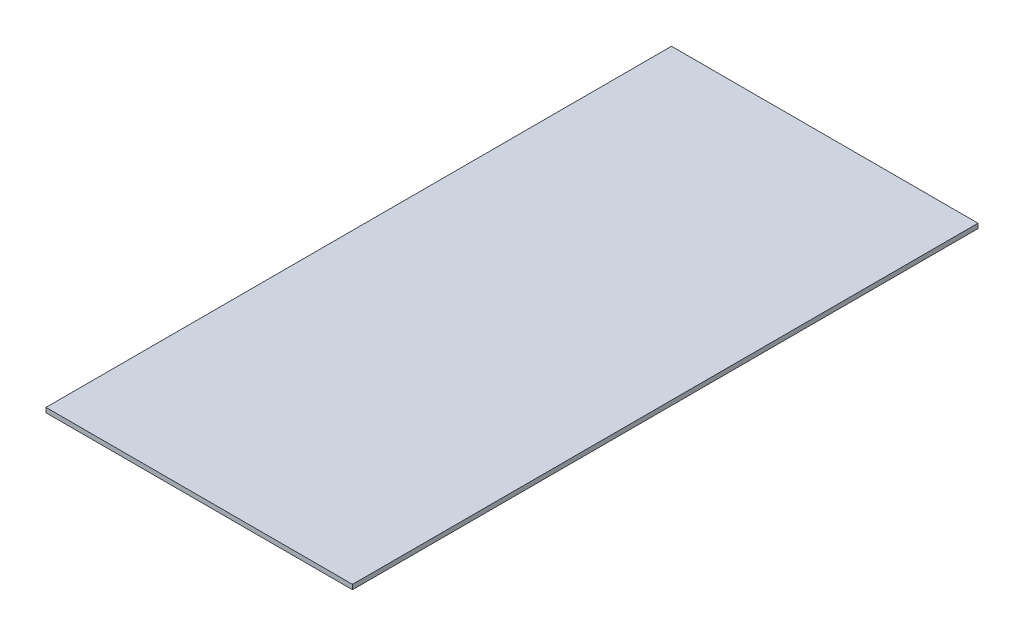
SolidWorks part; units mm, degrees
ref_plane "Front Plane" through (0, 0, 0) normal (0, 0, 1) x (1, 0, 0)
ref_plane "Top Plane" through (0, 0, 0) normal (0, 1, 0) x (1, 0, 0)
ref_plane "Right Plane" through (0, 0, 0) normal (1, 0, 0) x (0, 0, -1)
sketch "Sketch1" plane through (0, 0, 0) normal (0, 1, 0) x (1, 0, 0)
  line L1 (0, 0) -> (196, 0)
  line L2 (0, 0) -> (0, 400)
  line L3 (0, 400) -> (196, 400)
  line L4 (196, 0) -> (196, 400)
  dimension "D1" = 400
  dimension "D2" = 196
extrude "Boss-Extrude1" add sketch "Sketch1" along normal blind 3
